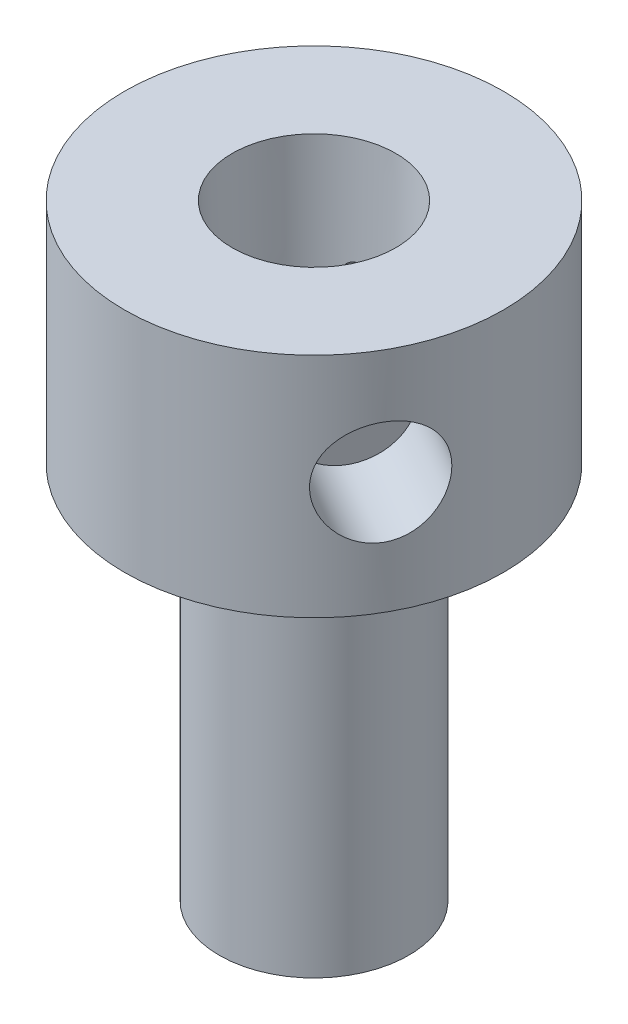
SolidWorks part; units mm, degrees
material "6061-T6 (SS)"
ref_plane "Front Plane" through (0, 0, 0) normal (0, 0, 1) x (1, 0, 0)
ref_plane "Top Plane" through (0, 0, 0) normal (0, 1, 0) x (1, 0, 0)
ref_plane "Right Plane" through (0, 0, 0) normal (1, 0, 0) x (0, 0, -1)
sketch "Sketch1" plane through (0, 0, 0) normal (0, 1, 0) x (1, 0, 0)
  circle A0 centre (0, 0) radius 15.875
  dimension "D1" = 31.75
extrude "Boss-Extrude1" add sketch "Sketch1" along normal blind 50.8
sketch "Sketch2" plane through (0, 0, 0) normal (0, -1, 0) x (-1, 0, 0)
  circle A0 centre (0, 0) radius 7.9375
  dimension "D1" = 15.875
extrude "Cut-Extrude1" cut sketch "Sketch2" against normal blind 31.75 flip side to cut
hole_wizard "1/8 (0.125) Diameter Hole1" positions "Sketch4" profile "Sketch5" hole size "1/8" standard "ANSI Inch" end condition through all
sketch "Sketch4" plane through (0, 50.8, 0) normal (0, 1, 0) x (1, 0, 0)
  point P0 (0, 0)
sketch "Sketch5" plane through (0, 50.8, 0) normal (1, 0, 0) x (0, 0, 1)
  line L0 (0, 0) -> (0, 50.8)
  line L1 (0, 50.8) -> (1.5875, 50.8)
  line L2 (1.5875, 50.8) -> (1.5875, 0)
  line L5 (1.5875, 0) -> (0, 0)
  line L11 (0, -6.35) -> (0, 107.95) construction
  dimension "Thru Hole Dia." = 3.175
  dimension "Thru Hole Depth" = 50.8
hole_wizard "1/4 NPT Tapped Hole1" positions "Sketch7" profile "Sketch6" size "1/4" standard "ANSI Inch"
sketch "Sketch7" plane through (0, 50.8, 0) normal (0, 1, 0) x (1, 0, 0)
  point P0 (0, 0)
sketch "Sketch6" plane through (0, 50.8, 0) normal (1, 0, 0) x (0, 0, 1)
  line L0 (0, 0) -> (0, 20.2757)
  line L1 (5.5626, 16.9333) -> (0, 20.2757)
  line L2 (-5.5626, 16.9333) -> (0, 20.2757) construction
  line L3 (5.5626, 16.9333) -> (5.5626, 9.906)
  line L4 (5.5626, 9.906) -> (6.558, 9.906)
  line L5 (6.558, 9.906) -> (6.8546, 0)
  line L6 (-6.558, 9.906) -> (-6.8546, 0) construction
  line L7 (6.8546, 0) -> (0, 0)
  line L8 (0, -6.35) -> (0, 107.95) construction
  line L11 (-5.5626, 9.906) -> (-6.558, 9.906) construction
  dimension "Tap Drill Dia." = 11.1252
  dimension "Tap Drill Depth" = 16.9333
  dimension "Thread Dia." = 13.7092
  dimension "Thread Angle" = 3.43
  dimension "Thread Depth" = 9.906
  dimension "Drill Angle" = 118
sketch "Sketch13" plane through (0, 0, 0) normal (0, -1, 0) x (1, 0, 0)
  circle A0 centre (0, 0) radius 6.35
  circle A1 centre (0, 0) radius 7.9375 construction
  dimension "D1" = 1.5875
extrude "Cut-Extrude5" cut sketch "Sketch13" along normal blind 1.5875 from offset 31.75 flip side to cut offset against normal yes
sketch "Sketch15" plane through (0, 0, 0) normal (0, 0, 1) x (1, 0, 0)
  circle A0 centre (0, 41.2071) radius 4.3656
  dimension "D1" = 8.7312
extrude "Cut-Extrude6" cut sketch "Sketch15" against normal up to next from offset 7.62 offset against normal yes
sketch "Sketch16" plane through (0, 0, -7.62) normal (0, 0, -1) x (-1, 0, 0)
  line L0 (4.3656, 41.2071) -> (-4.3656, 41.2071) construction
  circle A0 centre (2.54, 41.2071) radius 0.7938
  circle A1 centre (0, 41.2071) radius 4.3656 construction
  dimension "D1" = 1.5875
  dimension "D2" = 2.54
extrude "Cut-Extrude7" cut sketch "Sketch16" against normal up to next
pattern_circular "CirPattern1" count 2 every 120 about axis through (0, 50.8, 0) along (0, 1, 0) of "Cut-Extrude6", "Cut-Extrude7"
pattern_circular "CirPattern2" count 2 every 270 about axis through (0, 50.8, 0) along (0, 1, 0) of "Cut-Extrude6", "Cut-Extrude7"
